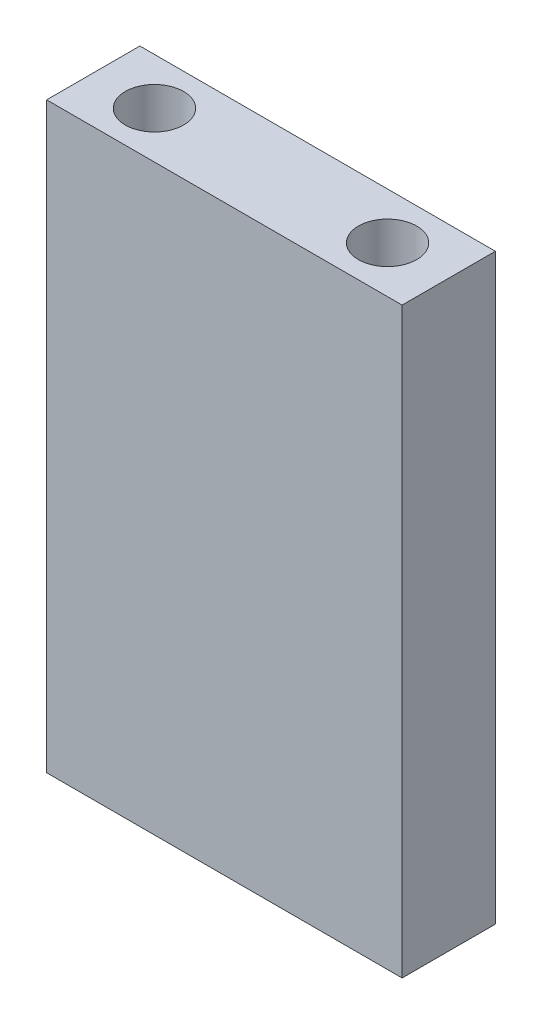
SolidWorks part; units mm, degrees
ref_plane "Front Plane" through (0, 0, 0) normal (0, 0, 1) x (1, 0, 0)
ref_plane "Top Plane" through (0, 0, 0) normal (0, 1, 0) x (1, 0, 0)
ref_plane "Right Plane" through (0, 0, 0) normal (1, 0, 0) x (0, 0, -1)
sketch "Sketch1" plane through (0, 0, 0) normal (0, 0, 1) x (1, 0, 0)
  line L1 (-7.625, 12.5) -> (7.625, 12.5)
  line L2 (-7.625, 12.5) -> (-7.625, -12.5)
  line L3 (-7.625, -12.5) -> (7.625, -12.5)
  line L4 (7.625, 12.5) -> (7.625, -12.5)
  line L5 (-7.625, 12.5) -> (7.625, -12.5) construction
  line L6 (-7.625, -12.5) -> (7.625, 12.5) construction
  point P0 (0, 0)
  dimension "D1" = 25
  dimension "D2" = 15.25
extrude "Boss-Extrude1" add sketch "Sketch1" along normal mid plane 4
sketch "Sketch3" plane through (0, 12.5, 0) normal (0, 1, 0) x (1, 0, 0)
  line L0 (0, -2.2) -> (0, 2.2) construction
  circle A0 centre (-5, 0) radius 1.25
  circle A1 centre (5, 0) radius 1.25
  dimension "D2" = 5
extrude "Cut-Extrude1" cut sketch "Sketch3" against normal blind 4 contours A0 | A1
equation "\"testbed_height\" = 91.50mm"
equation "\"plate_thickness\" = 4mm"
equation "\"main_body_splay_length\" = 48.5mm"
equation "\"splay_shaft_length_no_wires\" = 10mm"
equation "\"splay_shaft_length_wires\" = 6.5mm"
equation "\"timing_pulley_offset\" = 0mm"
equation "\"effective_motor_length\" = \"timing_pulley_offset\" + \"splay_shaft_length_no_wires\" + \"main_body_splay_length\""
equation "\"total_mounting_length\" = \"testbed_height\" - \"effective_motor_length\" - \"80_20_side\""
equation "\"mounting_vertical_portion_height\" = \"total_mounting_length\" - 2 * \"plate_thickness\""
equation "\"D1@Sketch1\"=\"mounting_vertical_portion_height\""
equation "\"face_mount_width\" = 15.25mm"
equation "\"D2@Sketch1\"=\"face_mount_width\""
equation "\"D1@Boss-Extrude1\"=\"plate_thickness\""
equation "\"center_dist_to_face_mount_vertical_screws\" = 5mm"
equation "\"D2@Sketch3\"=\"center_dist_to_face_mount_vertical_screws\""
